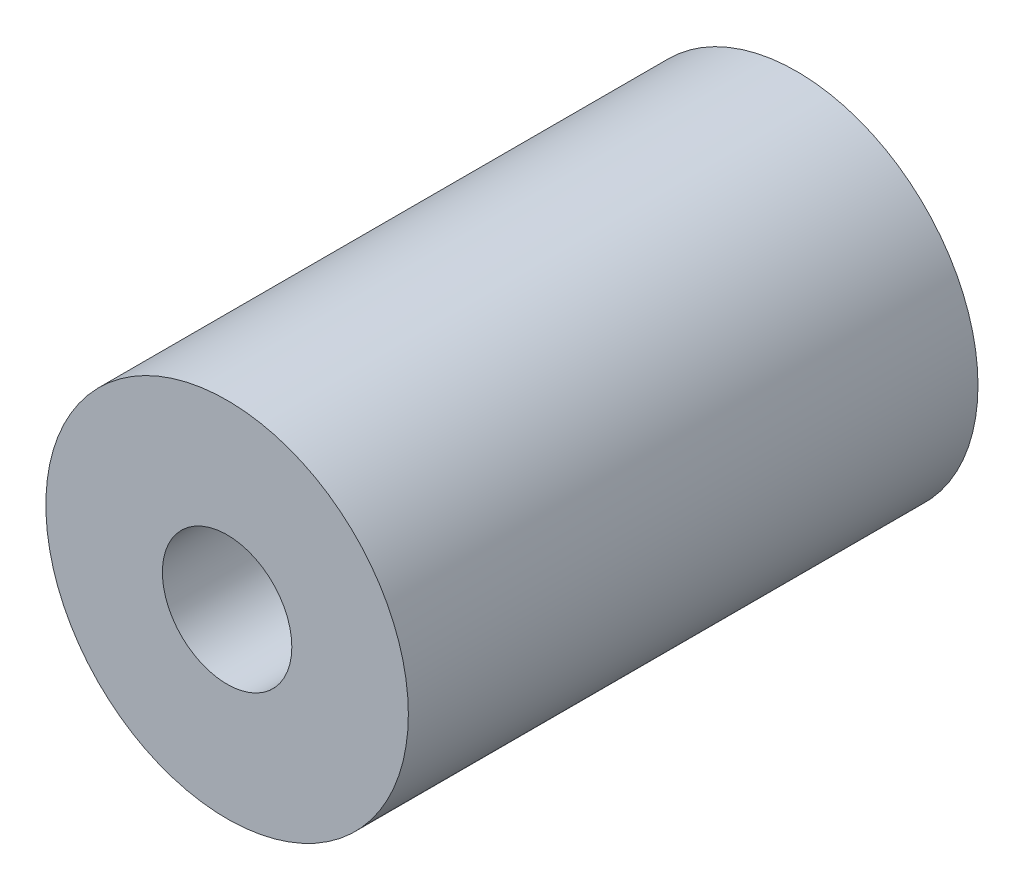
SolidWorks part; units mm, degrees
material "7075-T6 (SN)"
ref_plane "前视基准面" through (0, 0, 0) normal (0, 0, 1) x (1, 0, 0)
ref_plane "上视基准面" through (0, 0, 0) normal (0, 1, 0) x (1, 0, 0)
ref_plane "右视基准面" through (0, 0, 0) normal (1, 0, 0) x (0, 0, -1)
sketch "Sketch1" plane through (0, 0, 0) normal (0, 0, 1) x (1, 0, 0)
  circle A0 centre (0, 0) radius 7
  dimension "D1" = 14
extrude "Boss-Extrude1" add sketch "Sketch1" along normal mid plane 22
sketch "Sketch2" plane through (0, 0, 11) normal (0, 0, 1) x (1, 0, 0)
  circle A0 centre (0, 0) radius 2.5
  dimension "D1" = 5
extrude "Cut-Extrude1" cut sketch "Sketch2" against normal blind 6.5
sketch "Sketch3" plane through (0, 0, -11) normal (0, 0, -1) x (-1, 0, 0)
  circle A0 centre (0, 0) radius 4
  dimension "D1" = 8
extrude "Cut-Extrude2" cut sketch "Sketch3" against normal blind 6.5
